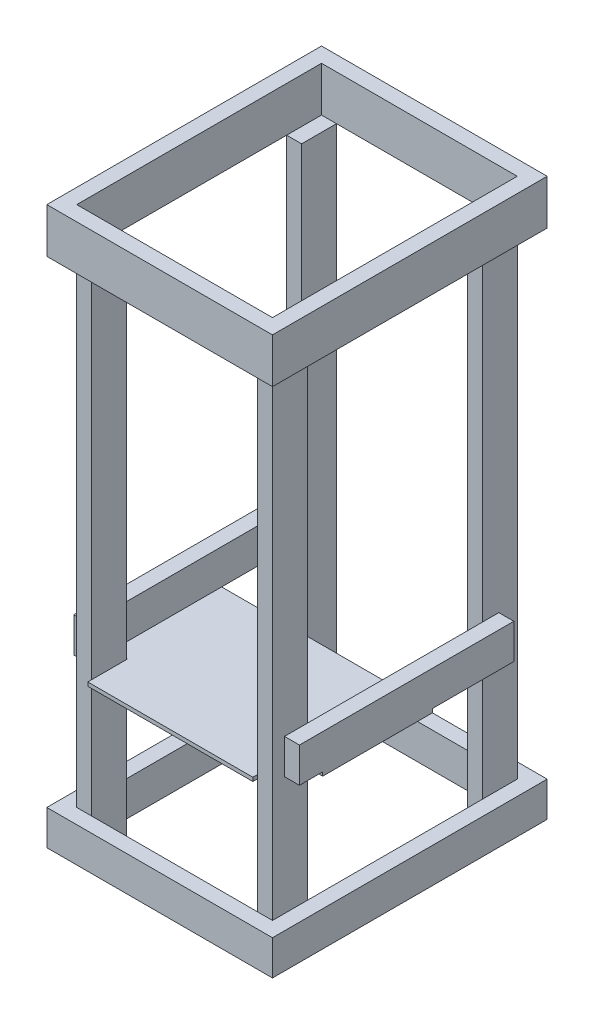
SolidWorks part; units mm, degrees
ref_plane "Front Plane" through (0, 0, 0) normal (0, 0, 1) x (1, 0, 0)
ref_plane "Top Plane" through (0, 0, 0) normal (0, 1, 0) x (1, 0, 0)
ref_plane "Right Plane" through (0, 0, 0) normal (1, 0, 0) x (0, 0, -1)
sketch "Sketch1" plane through (0, 0, 0) normal (0, 1, 0) x (1, 0, 0)
  line L0 (-130.4222, 311.9) -> (-130.4222, 350) construction
  line L1 (-287.5, 350) -> (287.5, 350)
  line L2 (-287.5, 350) -> (-287.5, -350)
  line L3 (-287.5, -350) -> (287.5, -350)
  line L4 (287.5, 350) -> (287.5, -350)
  line L5 (-287.5, 350) -> (287.5, -350) construction
  line L6 (-287.5, -350) -> (287.5, 350) construction
  line L7 (-249.4, 311.9) -> (249.4, 311.9)
  line L8 (-249.4, 311.9) -> (-249.4, -311.9)
  line L9 (-249.4, -311.9) -> (249.4, -311.9)
  line L10 (249.4, 311.9) -> (249.4, -311.9)
  line L11 (-249.4, 311.9) -> (249.4, -311.9) construction
  line L12 (-249.4, -311.9) -> (249.4, 311.9) construction
  line L14 (-249.4, 37.6035) -> (-287.5, 37.6035) construction
  line L16 (-62.8311, -311.9) -> (-62.8311, -350) construction
  line L18 (249.4, -90.9147) -> (287.5, -90.9147) construction
  point P0 (0, 0)
  point P6 (0, 0)
  dimension "D1" = 575
  dimension "D2" = 700
  dimension "D3" = 38.1
extrude "Boss-Extrude1" add sketch "Sketch1" along normal blind 114.3
sketch "Sketch2" plane through (0, 0, 0) normal (0, -1, 0) x (1, 0, 0)
  line L1 (-249.4, 311.9) -> (-211.3, 311.9)
  line L2 (-249.4, 311.9) -> (-249.4, 223)
  line L3 (-249.4, 223) -> (-211.3, 223)
  line L4 (-211.3, 311.9) -> (-211.3, 223)
  line L5 (-249.4, -311.9) -> (-211.3, -311.9)
  line L6 (-249.4, -311.9) -> (-249.4, -223)
  line L7 (-249.4, -223) -> (-211.3, -223)
  line L8 (-211.3, -311.9) -> (-211.3, -223)
  line L9 (249.4, 311.9) -> (211.3, 311.9)
  line L10 (249.4, 311.9) -> (249.4, 223)
  line L11 (249.4, 223) -> (211.3, 223)
  line L12 (211.3, 311.9) -> (211.3, 223)
  line L19 (249.4, -311.9) -> (211.3, -311.9)
  line L20 (249.4, -311.9) -> (249.4, -223)
  line L21 (249.4, -223) -> (211.3, -223)
  line L22 (211.3, -311.9) -> (211.3, -223)
  dimension "D1" = 38.1
  dimension "D2" = 88.9
extrude "Boss-Extrude2" add sketch "Sketch2" along normal blind 1305 separate body
sketch "Sketch3" plane through (0, -1305, 0) normal (0, -1, 0) x (1, 0, 0)
  line L0 (249.4, -311.9) -> (-249.4, -311.9) construction
  line L1 (249.4, 311.9) -> (249.4, -311.9) construction
  line L2 (-249.4, 311.9) -> (249.4, 311.9) construction
  line L3 (-249.4, -311.9) -> (-249.4, 311.9) construction
  line L4 (287.5, -350) -> (287.5, 350)
  line L5 (287.5, 350) -> (-287.5, 350)
  line L6 (-287.5, 350) -> (-287.5, -350)
  line L7 (-287.5, -350) -> (287.5, -350)
  line L8 (287.5, -350) -> (287.5, 350)
  line L9 (287.5, 350) -> (-287.5, 350)
  line L10 (-287.5, 350) -> (-287.5, -350)
  line L11 (-287.5, -350) -> (287.5, -350)
  line L12 (249.4, -311.9) -> (-249.4, -311.9)
  line L13 (249.4, 311.9) -> (249.4, -311.9)
  line L14 (-249.4, 311.9) -> (249.4, 311.9)
  line L15 (-249.4, -311.9) -> (-249.4, 311.9)
  dimension "D1" = 0
extrude "Boss-Extrude3" add sketch "Sketch3" against normal blind 88.9
ref_plane "Plane1" through (0, -914.1, 0) normal (0, 1, 0) x (1, 0, 0)
sketch "Sketch7" plane through (0, -914.1, 0) normal (0, 1, 0) x (1, 0, 0)
  line L0 (-249.4, 264.9186) -> (-287.5, 264.9186)
  line L1 (-249.4, 311.9) -> (-249.4, -311.9) construction
  line L2 (-287.5, 350) -> (-287.5, -350) construction
  line L3 (-287.5, 264.9186) -> (-287.5, -281.3159)
  line L4 (-287.5, -281.3159) -> (-249.4, -281.3159)
  line L5 (-249.4, 311.9) -> (-249.4, -311.9) construction
  line L6 (-249.4, -281.3159) -> (-249.4, 264.9186)
  line L7 (249.4, 264.9186) -> (287.5, 264.9186)
  line L8 (249.4, -311.9) -> (249.4, 311.9) construction
  line L9 (287.5, -350) -> (287.5, 350) construction
  line L10 (287.5, 264.9186) -> (287.5, -281.3159)
  line L11 (287.5, -281.3159) -> (249.4, -281.3159)
  line L12 (249.4, -281.3159) -> (249.4, 264.9186)
extrude "Boss-Extrude4" add sketch "Sketch7" along normal blind 88.9
sketch "Sketch8" plane through (0, -914.1, 0) normal (0, -1, 0) x (1, 0, 0)
  line L1 (287.5, -350) -> (287.5, 350) construction
  line L7 (-287.5, 350) -> (-287.5, -350) construction
  line L8 (-287.5, 222) -> (-287.5, -57.4)
  line L9 (-287.5, -57.4) -> (287.5, -57.4)
  line L10 (287.5, -57.4) -> (287.5, 222)
  line L16 (287.5, 281.3159) -> (287.5, -264.9186) construction
  line L17 (-287.5, -264.9186) -> (-287.5, 281.3159) construction
  line L18 (-287.5, 222) -> (-210.3, 222)
  line L19 (-210.3, 222) -> (-210.3, 322.8564)
  line L20 (-210.3, 322.8564) -> (210.3, 322.8564)
  line L21 (210.3, 322.8564) -> (210.3, 222)
  line L22 (210.3, 222) -> (287.5, 222)
  line L23 (211.3, 223) -> (249.4, 223) construction
  line L24 (211.3, 311.9) -> (211.3, 223) construction
  line L25 (-211.3, 223) -> (-211.3, 311.9) construction
  line L26 (-249.4, 223) -> (-211.3, 223) construction
  point P10 (287.5, 209.2659)
  dimension "D1" = 279.4
  dimension "D2" = 1
  dimension "D3" = 1
  dimension "D4" = 1
extrude "Boss-Extrude8" add sketch "Sketch8" along normal blind 9.525
